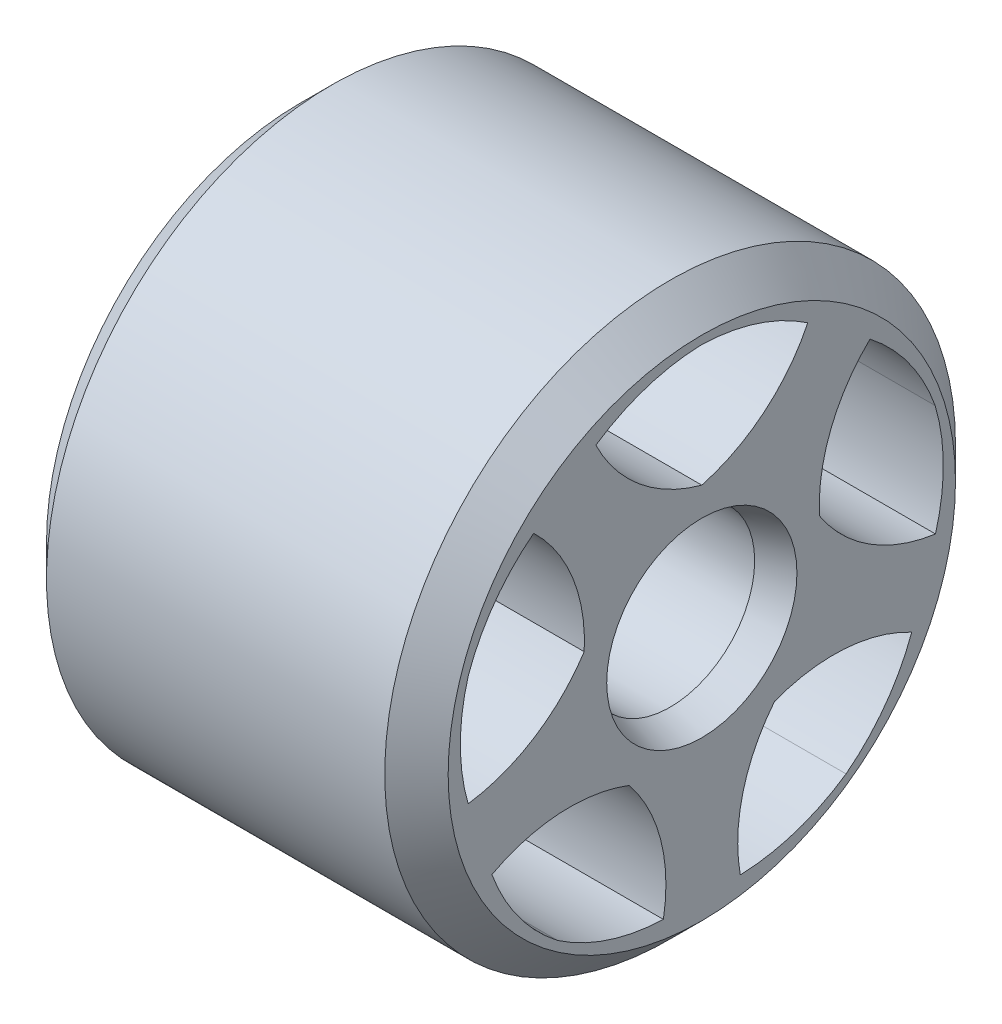
SolidWorks part; units mm, degrees
ref_plane "Front Plane" through (0, 0, 0) normal (0, 0, 1) x (1, 0, 0)
ref_plane "Top Plane" through (0, 0, 0) normal (0, 1, 0) x (1, 0, 0)
ref_plane "Right Plane" through (0, 0, 0) normal (1, 0, 0) x (0, 0, -1)
sketch "Sketch1" plane through (0, 0, 0) normal (1, 0, 0) x (0, 0, -1)
  circle A0 centre (0, 0) radius 13.5
  circle A1 centre (0, 0) radius 4
  dimension "D1" = 27
  dimension "D2" = 8
extrude "Boss-Extrude1" add sketch "Sketch1" along normal mid plane 19
sketch "Sketch2" plane through (0, 0, 0) normal (1, 0, 0) x (0, 0, -1)
  line L0 (0, 0) -> (0, 14.8201) construction
  arc A0 (0, 5.8497) -> (-5.0122, 9.994) centre (2.0377, 13.4173) cw
  arc A1 (-5.0122, 9.994) -> (0, 11.6087) centre (0.2591, 2.218) cw
  arc A2 (5.0122, 9.994) -> (0, 11.6087) centre (-0.2591, 2.218) ccw
  arc A3 (0, 5.8497) -> (5.0122, 9.994) centre (-2.0377, 13.4173) ccw
extrude "Cut-Extrude1" cut sketch "Sketch2" along normal through all both and the other way through all
pattern_circular "CirPattern1" count 5 over 360 about axis through (0, 0, 0) along (1, 0, 0) of "Cut-Extrude1"
chamfer "Chamfer1" distance 1.5 angle 45 2 edges at (9.5, 0, -13.5) (-9.5, 0, -13.5)
sketch "Sketch4" plane through (0, 0, 0) normal (1, 0, 0) x (0, 0, -1)
  circle A0 centre (0, 0) radius 13.5
  circle A1 centre (0, 0) radius 13.2
  circle A2 centre (0, 0) radius 13.5 construction
  dimension "D1" = 0.3
chamfer "Chamfer2" distance 0.5 distance2 1.5 1 edges at (9.5, 0, -4)
equation "\"axis_diameter\"=5.66"
equation "\"padding\"=0.5"
